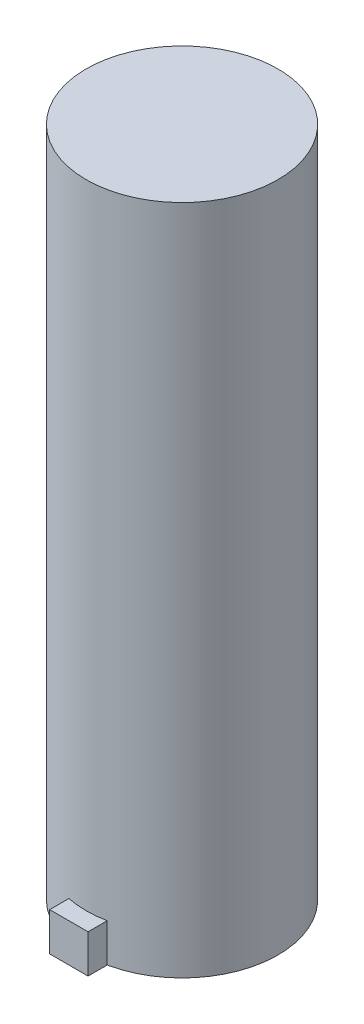
SolidWorks part; units mm, degrees
ref_plane "Front Plane" through (0, 0, 0) normal (0, 0, 1) x (1, 0, 0)
ref_plane "Top Plane" through (0, 0, 0) normal (0, 1, 0) x (1, 0, 0)
ref_plane "Right Plane" through (0, 0, 0) normal (1, 0, 0) x (0, 0, -1)
sketch "Sketch1" plane through (0, 0, 0) normal (0, 0, 1) x (1, 0, 0)
  line L0 (0, 0) -> (10, 0)
  line L1 (10, 0) -> (10, 70)
  line L2 (10, 70) -> (0, 70)
  line L3 (0, 70) -> (0, 0)
  dimension "D1" = 70
  dimension "D2" = 10
revolve "Revolve1" add sketch "Sketch1" angle 360 about L3
sketch "Sketch2" plane through (0, 0, 0) normal (0, -1, 0) x (1, 0, 0)
  line L0 (0, 0) -> (0, 14.0066) construction
  line L1 (-2, 11.798) -> (-2, 9.798)
  line L2 (-2, 11.798) -> (2, 11.798)
  line L3 (2, 11.798) -> (2, 9.798)
  circle A0 centre (0, 0) radius 10 construction
  arc A1 (2, 9.798) -> (-2, 9.798) centre (0, 0) ccw
  dimension "D1" = 2
  dimension "D2" = 4
extrude "Boss-Extrude1" add sketch "Sketch2" against normal blind 4 separate body
